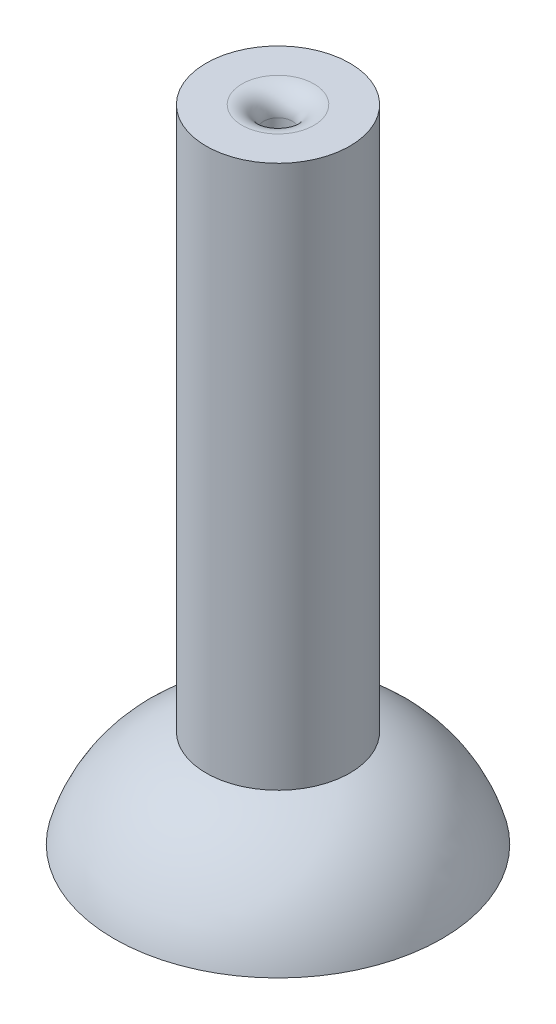
SolidWorks part; units mm, degrees
ref_plane "Front Plane" through (0, 0, 0) normal (0, 0, 1) x (1, 0, 0)
ref_plane "Top Plane" through (0, 0, 0) normal (0, 1, 0) x (1, 0, 0)
ref_plane "Right Plane" through (0, 0, 0) normal (1, 0, 0) x (0, 0, -1)
sketch "Sketch1" plane through (0, 0, 0) normal (0, 0, 1) x (1, 0, 0)
  line L0 (0, -4.4743) -> (0, 0) construction
  line L1 (-1, 35) -> (0, 35)
  line L2 (-5, 40) -> (-1, 40)
  line L3 (-5, 40) -> (-5, 2.2286)
  line L4 (-1, 40) -> (-1, 35)
  line L5 (0, 35) -> (0, 0)
  line L6 (0, -4.4743) -> (-1.8178, -4.4743) construction
  line L7 (-1.8178, -4.4743) -> (-1.8178, -7.1853) construction
  line L8 (-11.4, -4.5532) -> (-9.9, -4.5532)
  line L9 (0, 0) -> (-3.0003, 0)
  line L10 (0, 0) -> (0, 40) construction
  line L11 (0, 40) -> (-1, 40) construction
  line L12 (-3.0003, 0) -> (-4.9838, 0.7031)
  arc A0 (-4.9838, 0.7031) -> (-9.9, -4.5532) centre (-1.8178, -7.1853) ccw
  arc A1 (-11.4, -4.5532) -> (-5, 2.2286) centre (-1.8178, -7.1853) cw
  dimension "D1" = 1
  dimension "D2" = 5
  dimension "D5" = 8.5
  dimension "D7" = 2.7109
  dimension "D3" = 4
  dimension "D4" = 1.5
  dimension "D6" = 40
  dimension "D8" = 4.4743
  dimension "D9" = 1.8178
  dimension "D10" = 1.9835
  dimension "D11" = 9.3249
  dimension "D12" = 7.1971
revolve "Revolve1" add sketch "Sketch1" angle 360 about L0
sketch "Sketch2" plane through (0, 0, 0) normal (0, -1, 0) x (1, 0, 0)
  line L0 (-1.5, 2) -> (1.5, -2) construction
  line L1 (-1.5, 2) -> (1.5, 2)
  line L2 (-1.5, 2) -> (-1.5, -2)
  line L3 (-1.5, -2) -> (1.5, -2)
  line L4 (1.5, 2) -> (1.5, -2)
  circle A0 centre (0, 0) radius 2.5
  point P7 (0, 0)
  dimension "D1" = 3
  dimension "D2" = 5
  dimension "D3" = 5
extrude "Cut-Extrude1" cut sketch "Sketch2" against normal blind 5 contours L1 A0 | L1 L0 L4 | L0 L2 L3 | L3 A0
fillet "Fillet1" radius 1.5 1 edges at (0, 40, -1)
